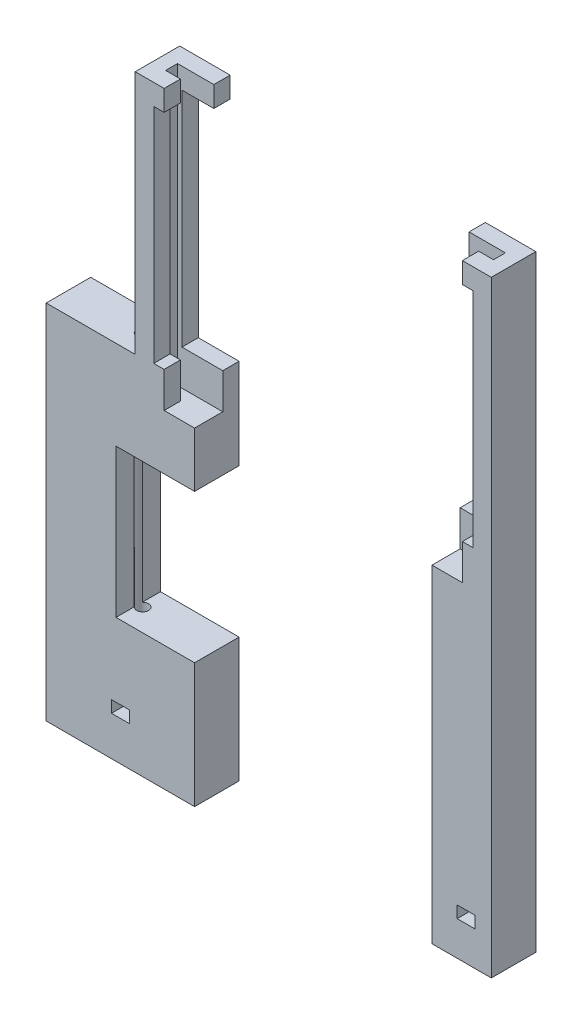
SolidWorks part; units mm, degrees
ref_plane "Alzado" through (0, 0, 0) normal (0, 0, 1) x (1, 0, 0)
ref_plane "Planta" through (0, 0, 0) normal (0, 1, 0) x (1, 0, 0)
ref_plane "Vista lateral" through (0, 0, 0) normal (1, 0, 0) x (0, 0, -1)
sketch "Croquis1" plane through (0, 0, 0) normal (0, 0, 1) x (1, 0, 0)
  line L1 (-110, 102.25) -> (110, 102.25)
  line L2 (-110, 102.25) -> (-110, -102.25)
  line L3 (-110, -102.25) -> (110, -102.25)
  line L4 (110, 102.25) -> (110, -102.25)
  line L5 (-110, 102.25) -> (110, -102.25) construction
  line L6 (-110, -102.25) -> (110, 102.25) construction
  point P0 (0, 0)
  dimension "D1" = 220
  dimension "D2" = 204.5
extrude "Saliente-Extruir1" add sketch "Croquis1" along normal blind 7
sketch "Croquis2" plane through (0, 0, 7) normal (0, 0, 1) x (1, 0, 0)
  line L0 (110, 102.25) -> (-110, 102.25) construction
  line L1 (-110, 102.25) -> (-110, -102.25) construction
  line L2 (-90, 62.25) -> (90, 62.25) construction
  line L4 (0, 102.25) -> (0, 0) construction
  line L5 (-110, 17.75) -> (110, 17.75) construction
  line L7 (110, -102.25) -> (110, 102.25) construction
  line L8 (-110, 32.75) -> (110, 32.75) construction
  line L9 (-110, -102.25) -> (110, -102.25) construction
  line L10 (-45, 102.25) -> (-45, -102.25) construction
  line L11 (45, 102.25) -> (45, -102.25) construction
  circle A0 centre (-90, 62.25) radius 11
  circle A1 centre (-90, 62.25) radius 14.5 construction
  circle A2 centre (90, 62.25) radius 14.5 construction
  circle A3 centre (90, 62.25) radius 11
  circle A4 centre (0, 62.25) radius 14.5 construction
  circle A5 centre (0, 62.25) radius 10
  circle A6 centre (90, 3.25) radius 14.5 construction
  circle A7 centre (90, 3.25) radius 11
  circle A8 centre (0, 3.25) radius 14.5 construction
  circle A9 centre (0, 3.25) radius 10
  circle A10 centre (-90, 3.25) radius 14.5 construction
  circle A11 centre (-90, 3.25) radius 11
  circle A12 centre (-45, -32.25) radius 14
  circle A13 centre (-45, -72.25) radius 14
  circle A14 centre (-45, -32.25) radius 16.5 construction
  circle A15 centre (-45, -72.25) radius 16.5 construction
  circle A16 centre (45, -59.6253) radius 11
  circle A17 centre (45, -59.6253) radius 20 construction
  dimension "D1" = 22
  dimension "D2" = 29
  dimension "D5" = 20
  dimension "D6" = 29
  dimension "D9" = 28
  dimension "D10" = 28
  dimension "D11" = 33
  dimension "D12" = 33
  dimension "D17" = 22
  dimension "D18" = 40
  dimension "D3" = 40
  dimension "D4" = 20
  dimension "D7" = 30
  dimension "D8" = 15
  dimension "D13" = 30
  dimension "D14" = 40
  dimension "D15" = 45
  dimension "D16" = 45
extrude "Cortar-Extruir1" cut sketch "Croquis2" against normal through all contours A11 | A0 | A5 | A3 | A7 | A9 | A16 | A12 | A13
sketch "Croquis3" plane through (0, 0, 7) normal (0, 0, 1) x (1, 0, 0)
  line L0 (-110, 90.25) -> (-104, 90.25)
  line L1 (-110, 102.25) -> (-110, -102.25) construction
  line L2 (-104, 90.25) -> (-104, 102.25)
  line L3 (110, 102.25) -> (-110, 102.25) construction
  line L4 (-104, 102.25) -> (-110, 102.25)
  line L5 (-110, 102.25) -> (-110, 90.25)
  dimension "D1" = 6
  dimension "D2" = 12
extrude "Cortar-Extruir2" cut sketch "Croquis3" against normal blind 10
sketch "Croquis4" plane through (0, 0, 7) normal (0, 0, 1) x (1, 0, 0)
  line L0 (110, -102.25) -> (110, 102.25) construction
  line L1 (-110, -102.25) -> (110, -102.25)
  line L2 (-110, -102.25) -> (-110, -95.25)
  line L3 (-110, -95.25) -> (110, -95.25)
  line L4 (110, -102.25) -> (110, -95.25)
  dimension "D1" = 7
extrude "Saliente-Extruir2" add sketch "Croquis4" along normal blind 150.6
sketch "Croquis5" plane through (0, -95.25, 0) normal (0, 1, 0) x (1, 0, 0)
  line L0 (110, -157.6) -> (110, -7) construction
  line L1 (-110, -157.6) -> (110, -157.6)
  line L2 (-110, -157.6) -> (-110, -150.6)
  line L3 (-110, -150.6) -> (110, -150.6)
  line L4 (110, -157.6) -> (110, -150.6)
  dimension "D1" = 7
extrude "Saliente-Extruir3" add sketch "Croquis5" along normal up to surface (197.5 mm away) up to face at (3, 102.25, 3.5)
sketch "Croquis6" plane through (0, 0, 150.6) normal (0, 0, -1) x (-1, 0, 0)
  line L1 (110, 102.25) -> (104, 102.25)
  line L2 (110, 102.25) -> (110, 90.25)
  line L3 (110, 90.25) -> (104, 90.25)
  line L4 (104, 102.25) -> (104, 90.25)
extrude "Cortar-Extruir3" cut sketch "Croquis6" against normal blind 150.6
sketch "Croquis7" plane through (0, 0, 157.6) normal (0, 0, 1) x (1, 0, 0)
  line L0 (3, 102.25) -> (3, -102.25) construction
  line L1 (110, 102.25) -> (-104, 102.25) construction
  line L2 (-110, -102.25) -> (110, -102.25) construction
  line L3 (-110, 90.25) -> (-110, -102.25) construction
  line L4 (-90, 72.25) -> (-17, 72.25) construction
  line L5 (-110, 57.25) -> (110, 57.25) construction
  line L6 (110, -102.25) -> (110, 102.25) construction
  line L7 (-110, 27.25) -> (110, 27.25) construction
  circle A0 centre (-90, 72.25) radius 2.5
  circle A1 centre (-17, 72.25) radius 2.5
  circle A2 centre (-53.5, 72.25) radius 2.5
  circle A3 centre (96, 72.25) radius 2.5
  circle A4 centre (59.5, 72.25) radius 2.5
  circle A5 centre (23, 72.25) radius 2.5
  circle A6 centre (96, 42.25) radius 2.5
  circle A7 centre (59.5, 42.25) radius 2.5
  circle A8 centre (23, 42.25) radius 2.5
  circle A9 centre (-17, 42.25) radius 2.5
  circle A10 centre (-53.5, 42.25) radius 2.5
  circle A11 centre (-90, 42.25) radius 2.5
  circle A12 centre (96, 12.25) radius 2.5
  circle A13 centre (59.5, 12.25) radius 2.5
  circle A14 centre (23, 12.25) radius 2.5
  circle A15 centre (-17, 12.25) radius 2.5
  circle A16 centre (-53.5, 12.25) radius 2.5
  circle A17 centre (-90, 12.25) radius 2.5
  dimension "D1" = 5
  dimension "D2" = 30
  dimension "D5" = 5
  dimension "D6" = 5
  dimension "D3" = 20
  dimension "D4" = 20
  dimension "D7" = 15
  dimension "D8" = 15
extrude "Cortar-Extruir4" cut sketch "Croquis7" against normal blind 10
sketch "Croquis8" plane through (0, -95.25, 0) normal (0, 1, 0) x (1, 0, 0)
  line L0 (-110, -150.6) -> (-110, -7) construction
  line L1 (-60, -95.6) -> (-40, -95.6)
  line L2 (-60, -95.6) -> (-60, -110.6)
  line L3 (-60, -110.6) -> (-40, -110.6)
  line L4 (-40, -95.6) -> (-40, -110.6)
  line L5 (40, -95.6) -> (60, -95.6)
  line L6 (40, -95.6) -> (40, -110.6)
  line L7 (40, -110.6) -> (60, -110.6)
  line L8 (60, -95.6) -> (60, -110.6)
  line L9 (110, -150.6) -> (110, -7) construction
  line L10 (-104, -150.6) -> (110, -150.6) construction
  line L11 (110, -150.6) -> (-110, -150.6) construction
  dimension "D1" = 15
  dimension "D2" = 20
  dimension "D3" = 20
  dimension "D4" = 50
  dimension "D5" = 50
  dimension "D6" = 40
  dimension "D7" = 40
  dimension "D8" = 15
extrude "Saliente-Extruir4" add sketch "Croquis8" along normal blind 197.5 contours L2 L1 L4 L3 | L6 L5 L8 L7
sketch "Croquis9" plane through (0, 102.25, 0) normal (0, 1, 0) x (1, 0, 0)
  line L1 (-55.2503, -101.0998) -> (55.2497, -101.0998)
  line L2 (-55.2503, -101.0998) -> (-55.2503, -105.0998)
  line L3 (-55.2503, -105.0998) -> (55.2497, -105.0998)
  line L4 (55.2497, -101.0998) -> (55.2497, -105.0998)
  line L5 (60, -95.6) -> (60, -110.6) construction
  line L8 (-60, -110.6) -> (-40, -110.6) construction
  dimension "D1" = 110.5
  dimension "D2" = 4
  dimension "D3" = 4.7503
  dimension "D4" = 5.5002
extrude "Cortar-Extruir5" cut sketch "Croquis9" against normal blind 94
sketch "Croquis10" plane through (0, 0, 110.6) normal (0, 0, 1) x (1, 0, 0)
  line L1 (-60, 102.25) -> (-40, 102.25) construction
  line L2 (-53.75, 95.25) -> (-40, 95.25)
  line L3 (-40, 102.25) -> (-40, -95.25) construction
  line L6 (40, 102.25) -> (60, 102.25) construction
  line L9 (40, 95.25) -> (53.75, 95.25)
  line L13 (-40, 20.25) -> (-53.75, 20.25)
  line L17 (40, 20.25) -> (53.75, 20.25)
  line L19 (-53.75, 95.25) -> (-53.75, 20.25)
  line L20 (40, 95.25) -> (40, 20.25)
  line L21 (53.75, 20.25) -> (53.75, 95.25)
  line L22 (-40, 95.25) -> (-40, 20.25)
  dimension "D1" = 75
  dimension "D2" = 7
  dimension "D3" = 7
  dimension "D4" = 75
  dimension "D6" = 13.75
  dimension "D9" = 13.75
sketch "Croquis11" plane through (0, 0, 157.6) normal (0, 0, 1) x (1, 0, 0)
  line L0 (0, 102.0159) -> (0, 102.25) construction
  line L1 (110, 102.25) -> (-104, 102.25) construction
  line L2 (0, -102.25) -> (0, 102.25) construction
  line L3 (-110, -102.25) -> (110, -102.25) construction
  line L7 (-53.5, 12.25) -> (-53.5, -102.25) construction
  circle A0 centre (-10, -77.25) radius 2.5
  circle A1 centre (10, -77.25) radius 2.5
  circle A2 centre (-63.5, -37.25) radius 2.5
  circle A3 centre (-43.5, -37.25) radius 2.5
  circle A4 centre (43.5, -37.25) radius 2.5
  circle A5 centre (63.5, -37.25) radius 2.5
  dimension "D1" = 5
  dimension "D2" = 5
  dimension "D7" = 5
  dimension "D8" = 5
  dimension "D3" = 10
  dimension "D4" = 10
  dimension "D5" = 25
  dimension "D6" = 25
  dimension "D9" = 10
  dimension "D10" = 10
  dimension "D11" = 65
  dimension "D12" = 65
extrude "Cortar-Extruir6" cut sketch "Croquis11" against normal blind 10
extrude "Cortar-Extruir7" cut sketch "Croquis10" against normal up to surface (15 mm away) up to face at (-50, 3.5, 95.6)
sketch "Croquis12" plane through (0, 102.25, 0) normal (0, 1, 0) x (1, 0, 0)
  line L0 (-60, -110.6) -> (-40, -110.6) construction
  line L1 (-40, -105.0998) -> (-50.2503, -105.0998)
  line L2 (-40, -105.0998) -> (-40, -110.6)
  line L3 (-40, -110.6) -> (-50.2503, -110.6)
  line L4 (-50.2503, -105.0998) -> (-50.2503, -110.6)
  line L5 (-55.2503, -101.0998) -> (-55.2503, -105.0998) construction
  line L6 (40, -110.6) -> (60, -110.6) construction
  line L7 (40, -105.0998) -> (50.2497, -105.0998)
  line L8 (40, -105.0998) -> (40, -110.6)
  line L9 (40, -110.6) -> (50.2497, -110.6)
  line L10 (50.2497, -105.0998) -> (50.2497, -110.6)
  line L11 (55.2497, -105.0998) -> (55.2497, -101.0998) construction
  dimension "D1" = 5
  dimension "D2" = 5
extrude "Cortar-Extruir8" cut sketch "Croquis12" against normal up to surface (94 mm away) up to face at (-47.6252, 8.25, 103.0998)
sketch "Croquis13" plane through (0, 102.25, 0) normal (0, 1, 0) x (1, 0, 0)
  line L0 (-55.2503, -101.0998) -> (-40, -101.0998) construction
  line L1 (-40, -95.6) -> (-43, -95.6)
  line L2 (-40, -95.6) -> (-40, -101.0998)
  line L3 (-40, -101.0998) -> (-43, -101.0998)
  line L4 (-43, -95.6) -> (-43, -101.0998)
  line L5 (55.2497, -101.0998) -> (40, -101.0998) construction
  line L6 (40, -95.6) -> (43, -95.6)
  line L7 (40, -95.6) -> (40, -101.0998)
  line L8 (40, -101.0998) -> (43, -101.0998)
  line L9 (43, -95.6) -> (43, -101.0998)
  dimension "D1" = 3
  dimension "D2" = 3
extrude "Cortar-Extruir9" cut sketch "Croquis13" against normal up to surface (7 mm away) up to face at (-46.875, 95.25, 98.3499)
sketch "Croquis14" plane through (0, 0, 110.6) normal (0, 0, 1) x (1, 0, 0)
  line L0 (-40, -10.25) -> (-51.4796, -10.25)
  line L1 (-40, 8.25) -> (-40, -95.25) construction
  line L2 (110, -95.25) -> (-110, -95.25) construction
  line L3 (-51.4796, -10.25) -> (-60, -10.25)
  line L4 (-60, 102.25) -> (-60, -95.25) construction
  line L5 (-60, -10.25) -> (-60, -60.25)
  line L6 (-60, -60.25) -> (-40, -60.25)
  line L7 (-40, -10.25) -> (-40, -60.25)
  dimension "D1" = 11.4796
  dimension "D2" = 85
  dimension "D3" = 50
extrude "Cortar-Extruir10" cut sketch "Croquis14" against normal up to surface (15 mm away) up to face at (-49.1875, 30.625, 95.6)
sketch "Croquis15" plane through (0, 0, 110.6) normal (0, 0, 1) x (1, 0, 0)
  line L0 (-60, 102.25) -> (-60, -10.25) construction
  line L1 (-60, 19.75) -> (-90, 19.75)
  line L2 (-60, 19.75) -> (-60, -10.25)
  line L3 (-60, -95.25) -> (-90, -95.25)
  line L4 (-90, 19.75) -> (-90, -95.25)
  line L5 (110, -95.25) -> (-110, -95.25) construction
  line L6 (-60, -10.25) -> (-66.476, -10.25)
  line L7 (-66.476, -10.25) -> (-66.476, -60.25)
  line L8 (-60, -60.25) -> (-40, -60.25) construction
  line L9 (-66.476, -60.25) -> (-60, -60.25)
  line L10 (-60, -60.25) -> (-60, -95.25)
  dimension "D1" = 30
  dimension "D2" = 115
extrude "Saliente-Extruir5" add sketch "Croquis15" against normal up to surface (15 mm away) up to face at (-49.1875, 51.875, 95.6)
sketch "Croquis16" plane through (0, -95.25, 0) normal (0, 1, 0) x (1, 0, 0)
  line L0 (110, -150.6) -> (-110, -150.6) construction
  line L1 (110, -7) -> (107, -7)
  line L2 (110, -7) -> (110, -150.6)
  line L3 (110, -150.6) -> (107, -150.6)
  line L4 (107, -7) -> (107, -150.6)
  line L6 (-110, -7) -> (-107, -7)
  line L7 (-110, -7) -> (-110, -150.6)
  line L8 (-110, -150.6) -> (-107, -150.6)
  line L9 (-107, -7) -> (-107, -150.6)
  dimension "D1" = 3
  dimension "D2" = 3
sketch "Croquis19" plane through (0, -95.25, 0) normal (0, 1, 0) x (1, 0, 0)
  line L0 (-90, -103.1) -> (60, -103.1) construction
  line L1 (-90, -95.6) -> (-90, -110.6) construction
  line L2 (60, -95.6) -> (60, -110.6) construction
  line L3 (60, -103.1) -> (51.5, -95.6) construction
  line L4 (43, -95.6) -> (60, -95.6) construction
  line L5 (51.5, -95.6) -> (51.5, -110.6) construction
  line L6 (40, -110.6) -> (60, -110.6) construction
  line L7 (-65, -95.6) -> (-65, -110.6) construction
  line L8 (-90, -95.6) -> (-40, -95.6) construction
  line L9 (-90, -110.6) -> (-40, -110.6) construction
  circle A0 centre (-65, -103.1) radius 2
  circle A1 centre (51.5, -103.1) radius 1.9998
  dimension "D1" = 3.9997
  dimension "D2" = 4
extrude "Cortar-Extruir13" cut sketch "Croquis19" along normal through all both and the other way through all
sketch "Croquis20" plane through (0, 102.25, 0) normal (0, 1, 0) x (1, 0, 0)
  line L0 (-110, -7) -> (-110, -150.6) construction
  line L1 (110, 0) -> (-110, 0)
  line L2 (110, 0) -> (110, -95.6)
  line L3 (110, -95.6) -> (-110, -95.6)
  line L4 (-110, 0) -> (-110, -95.6)
  line L5 (-90, -95.6) -> (-40, -95.6) construction
  line L6 (110, -7) -> (110, -150.6) construction
  line L7 (-110, -157.6) -> (110, -157.6)
  line L8 (-110, -157.6) -> (-110, -110.6)
  line L9 (-110, -110.6) -> (110, -110.6)
  line L10 (110, -157.6) -> (110, -110.6)
  line L11 (-60, -110.6) -> (-90, -110.6) construction
  line L12 (-110, -95.6) -> (-110, -110.6)
  line L14 (-110, -95.6) -> (-110, -110.6)
  line L16 (-90, -95.6) -> (-90, -110.6)
  line L18 (-40, -95.6) -> (-40, -110.6)
  line L20 (40, -95.6) -> (40, -110.6)
  line L22 (110, -95.6) -> (110, -110.6)
  line L24 (60, -95.6) -> (60, -110.6)
  line L25 (110, -95.6) -> (110, -110.6)
extrude "Cortar-Extruir14" cut sketch "Croquis20" against normal through all contours L2 L1 L4 L3 | L8 L7 L10 L9
sketch "Croquis21" plane through (0, -95.25, 0) normal (0, 1, 0) x (1, 0, 0)
  line L1 (-90, -95.6) -> (-110, -95.6)
  line L2 (-90, -95.6) -> (-90, -110.6)
  line L3 (-90, -110.6) -> (-110, -110.6)
  line L4 (-110, -95.6) -> (-110, -110.6)
  line L5 (-40, -110.6) -> (40, -110.6)
  line L6 (-40, -110.6) -> (-40, -95.6)
  line L7 (-40, -95.6) -> (40, -95.6)
  line L8 (40, -110.6) -> (40, -95.6)
  line L9 (60, -95.6) -> (110, -95.6)
  line L10 (60, -95.6) -> (60, -110.6)
  line L11 (60, -110.6) -> (110, -110.6)
  line L12 (110, -95.6) -> (110, -110.6)
extrude "Cortar-Extruir15" cut sketch "Croquis21" against normal through all
sketch "Croquis22" plane through (0, 0, 110.6) normal (0, 0, 1) x (1, 0, 0)
  line L1 (-68, -84.9939) -> (-62, -84.9939)
  line L2 (-68, -84.9939) -> (-68, -88.9939)
  line L3 (-68, -88.9939) -> (-62, -88.9939)
  line L4 (-62, -84.9939) -> (-62, -88.9939)
  line L5 (-90, -102.25) -> (-40, -102.25) construction
  line L6 (51.5002, -102.25) -> (51.5002, -97.3269) construction
  line L7 (48.5002, -86.6753) -> (54.5002, -86.6753)
  line L8 (48.5002, -86.6753) -> (48.5002, -90.6753)
  line L9 (48.5002, -90.6753) -> (54.5002, -90.6753)
  line L10 (54.5002, -86.6753) -> (54.5002, -90.6753)
  line L11 (40, -102.25) -> (60, -102.25) construction
  line L12 (49.5002, 8.25) -> (49.5002, -102.25) construction
  point P4 (-62, -86.9939)
  point P9 (-65, -102.25)
  dimension "D1" = 6
  dimension "D2" = 4
  dimension "D3" = 3
  dimension "D4" = 4
  dimension "D5" = 6
  dimension "D6" = 2
  dimension "D7" = 3
extrude "Cortar-Extruir16" cut sketch "Croquis22" against normal through all
